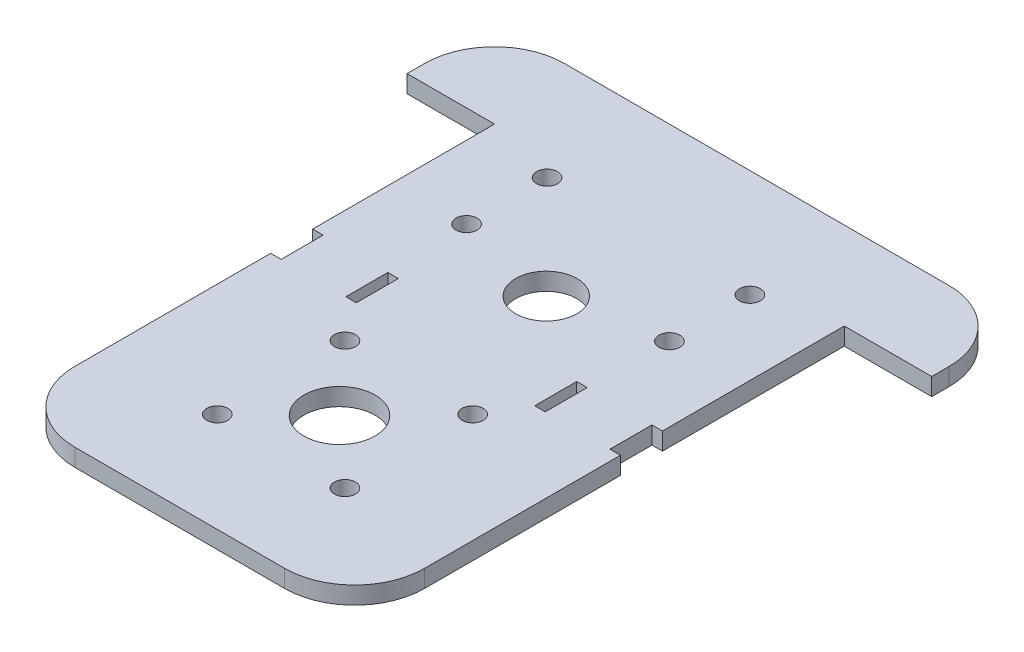
SolidWorks part; units mm, degrees
ref_plane "Front Plane" through (0, 0, 0) normal (0, 0, 1) x (1, 0, 0)
ref_plane "Top Plane" through (0, 0, 0) normal (0, 1, 0) x (1, 0, 0)
ref_plane "Right Plane" through (0, 0, 0) normal (1, 0, 0) x (0, 0, -1)
sketch "Sketch1" plane through (0, 0, 0) normal (0, 1, 0) x (1, 0, 0)
  line L0 (75, 0) -> (75, 200)
  line L5 (0, 0) -> (150, 0)
  line L6 (0, 0) -> (0, 200)
  line L7 (0, 200) -> (150, 200)
  line L8 (150, 0) -> (150, 200)
  line L9 (0, 200) -> (21.3255, 200)
  line L10 (75, 100) -> (93.746, 100)
  line L11 (25, 175) -> (0, 175)
  line L12 (25, 175) -> (25, 100)
  line L13 (25, 100) -> (0, 100)
  line L14 (25, 100) -> (25, 111)
  line L15 (25, 111) -> (28, 111)
  line L16 (28, 111) -> (28, 123)
  line L17 (28, 123) -> (25, 123)
  line L18 (49.5, 111) -> (46.5, 111)
  line L19 (46.5, 111) -> (46.5, 123)
  line L20 (46.5, 123) -> (49.5, 123)
  line L21 (49.5, 123) -> (49.5, 111)
  line L22 (100.5, 123) -> (100.5, 111)
  line L23 (103.5, 123) -> (100.5, 123)
  line L24 (103.5, 111) -> (103.5, 123)
  line L25 (100.5, 111) -> (103.5, 111)
  line L26 (122, 111) -> (122, 123)
  line L27 (125, 111) -> (122, 111)
  line L28 (122, 123) -> (125, 123)
  line L29 (125, 100) -> (150, 100)
  line L30 (125, 175) -> (125, 100)
  line L31 (125, 175) -> (150, 175)
  line L32 (75, 100) -> (57.246, 100)
  line L33 (57.246, 100) -> (57.246, 63.5)
  line L34 (57.246, 63.5) -> (93.746, 63.5)
  line L35 (93.746, 63.5) -> (93.746, 100)
  line L36 (0, 0) -> (0, 35)
  line L37 (0, 35) -> (150, 35)
  line L38 (125, 100) -> (125, 35)
  line L39 (25, 100) -> (25, 35)
  circle A0 centre (75, 139.7999) radius 8.7434
  circle A1 centre (57.246, 100) radius 3
  circle A2 centre (57.246, 63.5) radius 3
  circle A3 centre (93.746, 63.5) radius 3
  circle A4 centre (93.746, 100) radius 3
  circle A5 centre (75, 80.6749) radius 10.1723
  circle A6 centre (45.7717, 169.2372) radius 3
  circle A7 centre (103.7717, 169.2372) radius 3
  circle A8 centre (103.7717, 146.2372) radius 3
  circle A9 centre (45.7717, 146.2372) radius 3 construction
  circle A10 centre (45.7717, 169.2372) radius 3
  circle A11 centre (45.7717, 146.2372) radius 3
  point P59 (0, 0)
  point P60 (0, 0)
  point P61 (65.8928, 78.72)
  point P62 (45.8255, 174.6168)
  point P63 (45.8254, 151.33)
  point P64 (103.8209, 174.33)
  point P65 (119.9597, 113.2762)
  point P66 (0, 96.9328)
  point P67 (75, 72.7467)
  point P68 (0, 0)
  point P69 (75, 59.3388)
  point P70 (0, 0)
  point P71 (0, 0)
  point P72 (0, 0)
  point P73 (45.7717, 146.2372)
  point P74 (75, 156.012)
  point P75 (75, 139.7999)
  point P76 (0, 0)
  point P77 (0, 0)
  point P78 (0, 0)
  point P79 (0, 0)
  point P80 (0, 0)
  point P81 (0, 0)
  point P82 (75.496, 80.6749)
  point P83 (0, 0)
  point P84 (0, 0)
  point P87 (122, 123)
  point P88 (0, 0)
  point P89 (0, 0)
  point P90 (0, 0)
  point P91 (0, 0)
  point P92 (0, 0)
  dimension "D1" = 58
  dimension "D2" = 23
  dimension "D4" = 21.5
  dimension "D8" = 100
  dimension "D16" = 12
  dimension "D3" = 23
  dimension "D5" = 25
  dimension "D6" = 36.5
  dimension "D7" = 36.5
  dimension "D9" = 3
  dimension "D10" = 3
  dimension "D12" = 75
  dimension "D13" = 11
  dimension "D14" = 65
  dimension "D15" = 25
  dimension "D17" = 12
  dimension "D18" = 3
extrude "Boss-Extrude1" add sketch "Sketch1" along normal blind 5 contours A2 L33 A1 L32 L0 A0 L7 L6 L11 L12 L17 L16 L15 L13 L5 L34 L20 L21 L18 L19 | A4 L35 A3 L34 L0 L5 L8 L29 L30 L27 L26 L28 L31 L7 A0 L10 L25 L22 L23 L24 | A4 L10 L0 L34 A3 L35 | A2 L34 L0 L32 A1 L33
fillet "Fillet3" radius 20 1 edges at (0, 2.5, -200)
fillet "Fillet4" radius 20 1 edges at (150, 2.5, -200)
fillet "Fillet5" radius 20 2 edges at (125, 2.5, -35) (25, 2.5, -35)
